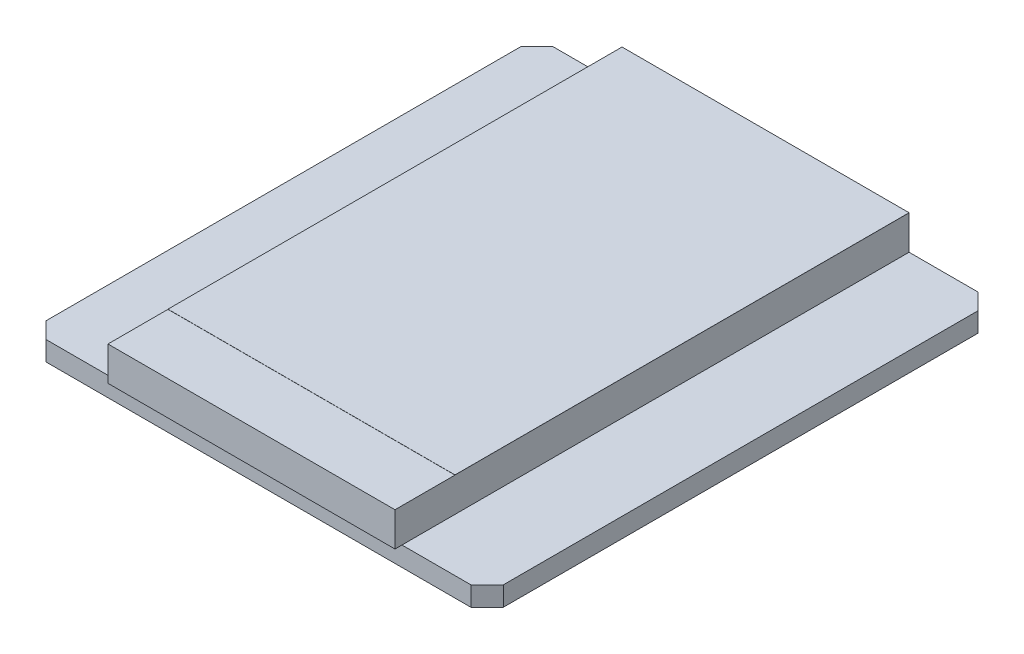
SolidWorks part; units mm, degrees
ref_plane "Спереди" through (0, 0, 0) normal (0, 0, 1) x (1, 0, 0)
ref_plane "Сверху" through (0, 0, 0) normal (0, 1, 0) x (1, 0, 0)
ref_plane "Справа" through (0, 0, 0) normal (1, 0, 0) x (0, 0, -1)
sketch "Эскиз1" plane through (0, 0, 0) normal (0, 1, 0) x (1, 0, 0)
  line L0 (-14.1, 14.635) -> (-13.1, 15.635)
  line L1 (-13.1, 15.635) -> (13.1, 15.635)
  line L2 (-14.1, 14.635) -> (-14.1, -14.635)
  line L3 (-13.1, -15.635) -> (13.1, -15.635)
  line L4 (14.1, 14.635) -> (14.1, -14.635)
  line L5 (-14.1, 15.635) -> (14.1, -15.635) construction
  line L6 (-14.1, -15.635) -> (14.1, 15.635) construction
  line L7 (13.1, 15.635) -> (14.1, 14.635)
  line L8 (14.1, -14.635) -> (13.1, -15.635)
  line L9 (-14.1, -14.635) -> (-13.1, -15.635)
  point P0 (0, 0)
  dimension "D1" = 31.27
  dimension "D2" = 28.2
extrude "Бобышка-Вытянуть1" add sketch "Эскиз1" along normal blind 1.2
sketch "Эскиз2" plane through (0, 1.2, 0) normal (0, 1, 0) x (1, 0, 0)
  line L0 (0, 15.635) -> (0, -15.635) construction
  line L1 (13.1, 15.635) -> (-13.1, 15.635) construction
  line L2 (-13.1, -15.635) -> (13.1, -15.635) construction
  line L4 (-8.85, 15.635) -> (8.85, 15.635)
  line L5 (-8.85, 15.635) -> (-8.85, -16.065)
  line L6 (-8.85, -16.065) -> (8.85, -16.065)
  line L7 (8.85, 15.635) -> (8.85, -16.065)
  dimension "D1" = 17.7
  dimension "D2" = 31.7
extrude "Бобышка-Вытянуть2" add sketch "Эскиз2" along normal blind 2.1 separate body contours L7 L6 L5 L4
sketch "Эскиз3" plane through (0, 3.3, 0) normal (0, 1, 0) x (1, 0, 0)
  line L0 (8.85, 15.635) -> (8.85, -16.065) construction
  line L1 (-8.85, 15.635) -> (8.85, 15.635)
  line L2 (-8.85, 15.635) -> (-8.85, -12.365)
  line L3 (-8.85, -12.365) -> (8.85, -12.365)
  line L4 (8.85, 15.635) -> (8.85, -12.365)
  dimension "D1" = 28
extrude "Бобышка-Вытянуть3" add sketch "Эскиз3" along normal blind 0.01 separate body
